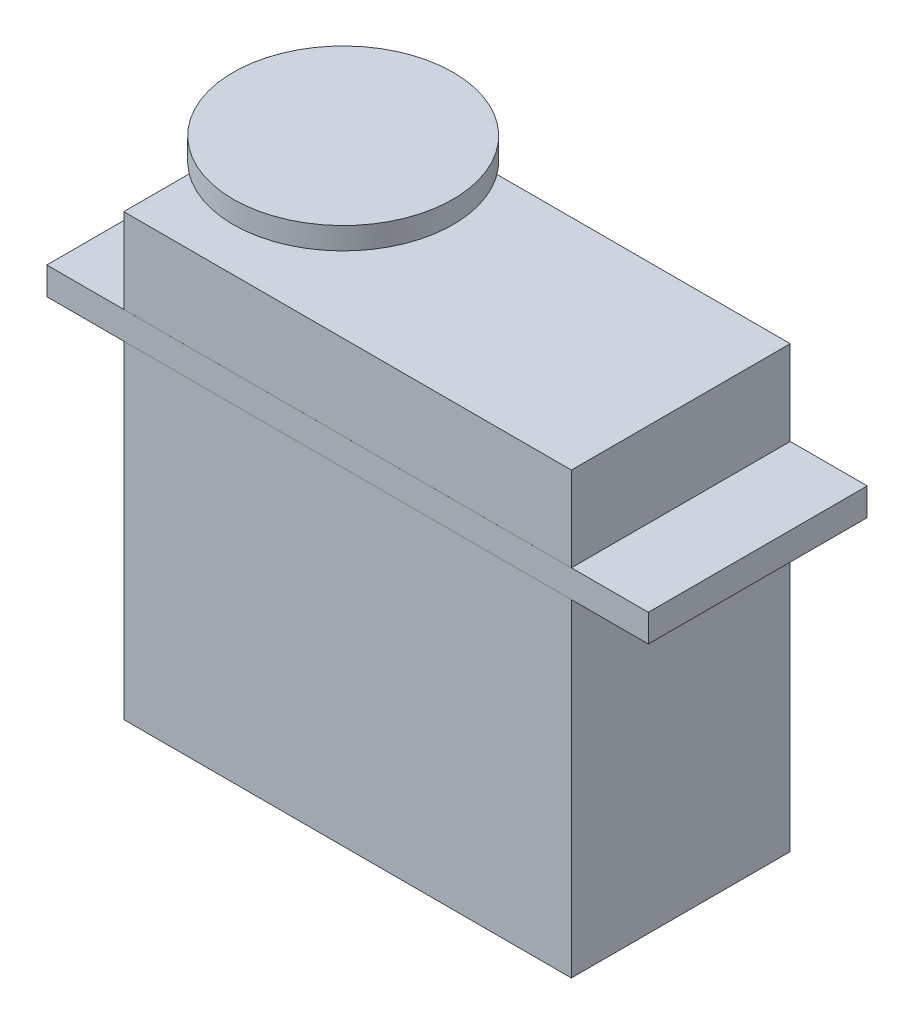
SolidWorks part; units mm, degrees
ref_plane "정면" through (0, 0, 0) normal (0, 0, 1) x (1, 0, 0)
ref_plane "윗면" through (0, 0, 0) normal (0, 1, 0) x (1, 0, 0)
ref_plane "우측면" through (0, 0, 0) normal (1, 0, 0) x (0, 0, -1)
sketch "스케치1" plane through (0, 0, 0) normal (0, 1, 0) x (1, 0, 0)
  line L1 (-20.35, 9.95) -> (20.35, 9.95)
  line L2 (-20.35, 9.95) -> (-20.35, -9.95)
  line L3 (-20.35, -9.95) -> (20.35, -9.95)
  line L4 (20.35, 9.95) -> (20.35, -9.95)
  line L5 (-20.35, 9.95) -> (20.35, -9.95) construction
  line L6 (-20.35, -9.95) -> (20.35, 9.95) construction
  point P0 (0, 0)
  dimension "D1" = 40.7
  dimension "D2" = 19.9
extrude "보스-돌출1" add sketch "스케치1" along normal blind 40
sketch "스케치2" plane through (0, 40, 0) normal (0, 1, 0) x (1, 0, 0)
  line L0 (-20.35, 9.95) -> (-20.35, -9.95) construction
  circle A0 centre (-10.35, 0) radius 3
  dimension "D1" = 6
  dimension "D2" = 10
extrude "보스-돌출2" add sketch "스케치2" along normal blind 6
sketch "스케치3" plane through (0, 40, 0) normal (0, 1, 0) x (1, 0, 0)
  line L0 (-20.35, 9.95) -> (-20.35, -9.95) construction
  line L1 (27.35, -9.9506) -> (-27.35, -9.9506)
  line L2 (27.35, -9.9506) -> (27.35, 9.9506)
  line L3 (27.35, 9.9506) -> (-27.35, 9.9506)
  line L4 (-27.35, -9.9506) -> (-27.35, 9.9506)
  line L5 (27.35, -9.9506) -> (-27.35, 9.9506) construction
  line L6 (27.35, 9.9506) -> (-27.35, -9.9506) construction
  point P0 (0, 0)
  dimension "D1" = 7
  dimension "D2" = 19.9012
extrude "보스-돌출3" add sketch "스케치3" against normal blind 2.5 from offset 7.7 offset against normal yes
sketch "스케치4" plane through (0, 46, 0) normal (0, 1, 0) x (1, 0, 0)
  circle A0 centre (-10.35, 0) radius 10
  dimension "D1" = 20
extrude "보스-돌출4" add sketch "스케치4" against normal blind 2
sketch "스케치5" plane through (0, 32.3, 0) normal (0, 1, 0) x (1, 0, 0)
  circle A0 centre (23.85, -7) radius 1.5
  circle A1 centre (23.85, 7) radius 1.5
